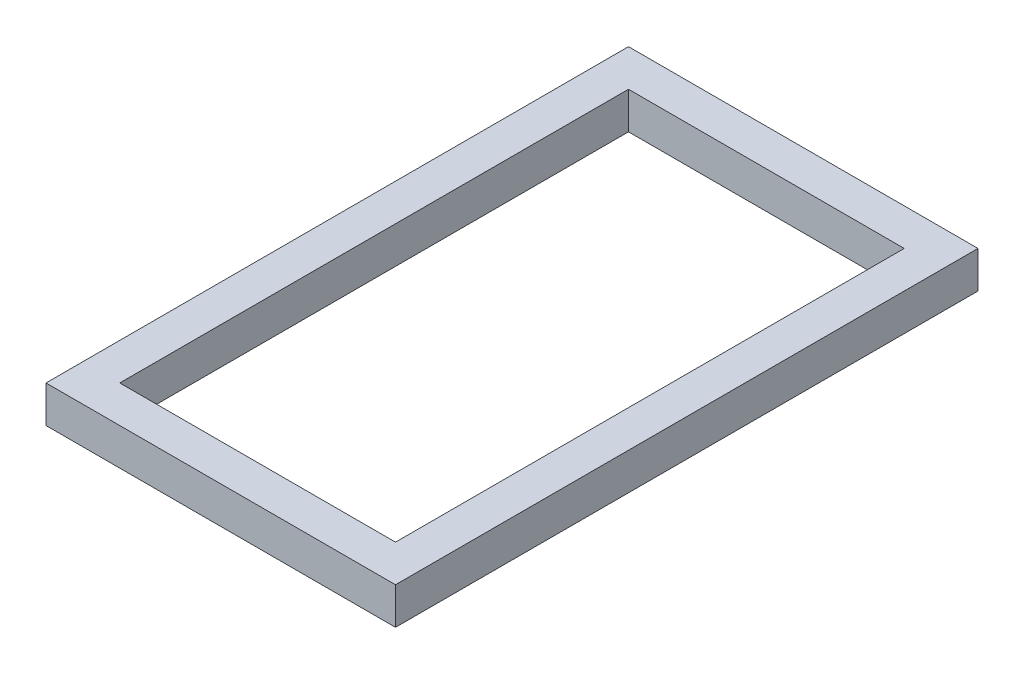
SolidWorks part; units mm, degrees
ref_plane "Front Plane" through (0, 0, 0) normal (0, 0, 1) x (1, 0, 0)
ref_plane "Top Plane" through (0, 0, 0) normal (0, 1, 0) x (1, 0, 0)
ref_plane "Right Plane" through (0, 0, 0) normal (1, 0, 0) x (0, 0, -1)
sketch "Sketch1" plane through (0, 0, 0) normal (0, 1, 0) x (1, 0, 0)
  line L0 (-71, 131) -> (71, 131)
  line L1 (-90, 150) -> (90, 150)
  line L2 (-90, 150) -> (-90, -150)
  line L3 (-90, -150) -> (90, -150)
  line L4 (90, 150) -> (90, -150)
  line L5 (-90, 150) -> (90, -150) construction
  line L6 (-90, -150) -> (90, 150) construction
  line L7 (71, 131) -> (71, -131)
  line L8 (-71, -131) -> (71, -131)
  line L9 (-71, 131) -> (-71, -131)
  point P0 (0, 0)
  dimension "D1" = 300
  dimension "D2" = 180
  dimension "D3" = 19
extrude "Boss-Extrude1" add sketch "Sketch1" along normal blind 19
